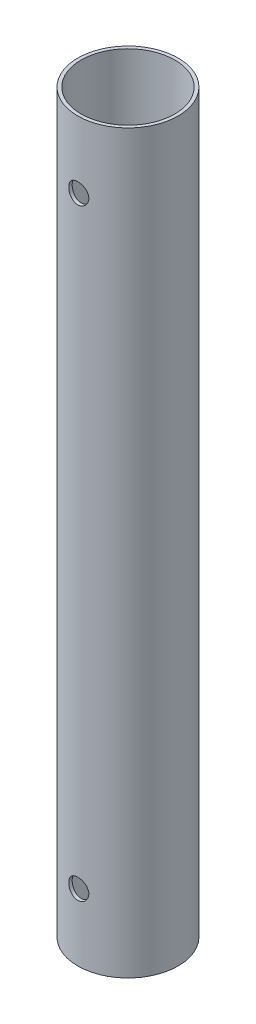
SolidWorks part; units mm, degrees
ref_plane "Front Plane" through (0, 0, 0) normal (0, 0, 1) x (1, 0, 0)
ref_plane "Top Plane" through (0, 0, 0) normal (0, 1, 0) x (1, 0, 0)
ref_plane "Right Plane" through (0, 0, 0) normal (1, 0, 0) x (0, 0, -1)
sketch "Sketch1" plane through (0, 0, 0) normal (0, 1, 0) x (1, 0, 0)
  circle A0 centre (0, 0) radius 14
  circle A1 centre (0, 0) radius 15
  dimension "D1" = 30
  dimension "D2" = 28
extrude "Boss-Extrude1" add sketch "Sketch1" along normal blind 220
sketch "Sketch2" plane through (0, 0, 0) normal (0, 0, 1) x (1, 0, 0)
  line L0 (15, 220) -> (-15, 220) construction
  circle A0 centre (0, 200) radius 3
  circle A1 centre (0, 20) radius 3
  dimension "D1" = 20
  dimension "D2" = 20
extrude "Cut-Extrude1" cut sketch "Sketch2" against normal mid plane 30
